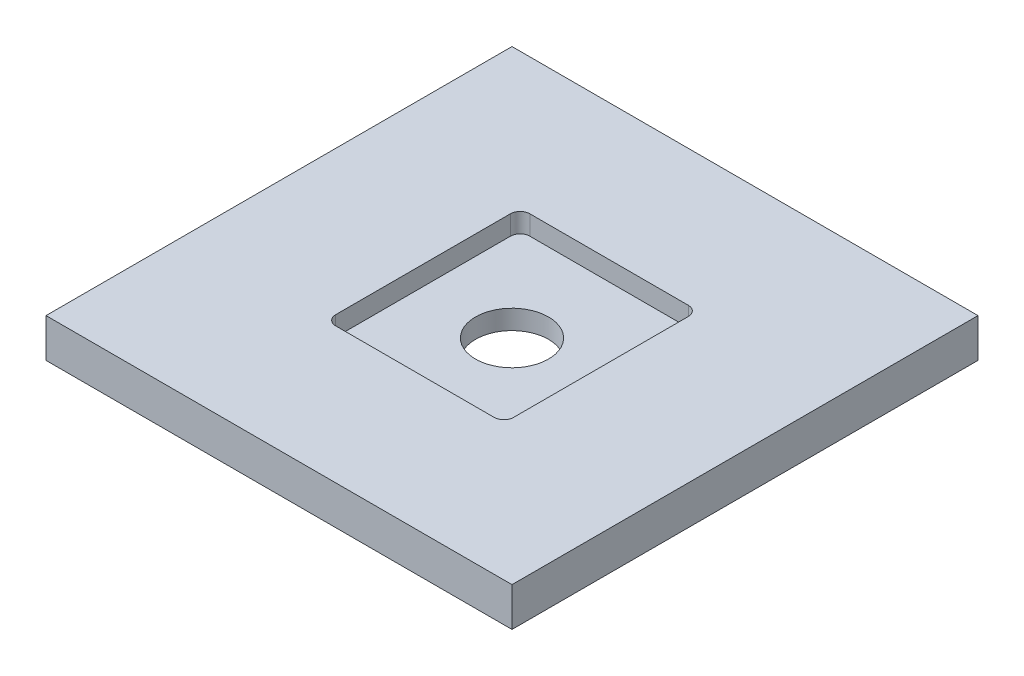
SolidWorks part; units mm, degrees
material "Plain Carbon Steel"
ref_plane "Front Plane" through (0, 0, 0) normal (0, 0, 1) x (1, 0, 0)
ref_plane "Top Plane" through (0, 0, 0) normal (0, 1, 0) x (1, 0, 0)
ref_plane "Right Plane" through (0, 0, 0) normal (1, 0, 0) x (0, 0, -1)
sketch "Sketch1" plane through (0, 0, 0) normal (0, 1, 0) x (1, 0, 0)
  line L1 (-152.4, 152.4) -> (152.4, 152.4)
  line L2 (-152.4, 152.4) -> (-152.4, -152.4)
  line L3 (-152.4, -152.4) -> (152.4, -152.4)
  line L4 (152.4, 152.4) -> (152.4, -152.4)
  line L5 (-152.4, 152.4) -> (152.4, -152.4) construction
  line L6 (-152.4, -152.4) -> (152.4, 152.4) construction
  line L7 (-58.1853, -63.5) -> (58.1853, -63.5)
  line L8 (-58.1853, -63.5) -> (-58.1853, 63.5)
  line L9 (-58.1853, 63.5) -> (58.1853, 63.5)
  line L10 (58.1853, -63.5) -> (58.1853, 63.5)
  line L11 (-58.1853, -63.5) -> (58.1853, 63.5) construction
  line L12 (-58.1853, 63.5) -> (58.1853, -63.5) construction
  point P0 (0, 0)
  point P6 (0, 0)
  dimension "D1" = 304.8
  dimension "D2" = 127
extrude "Sheet metal cutout" add sketch "Sketch1" along normal blind 12.7
fillet "cutout fillet" radius 6.35 4 edges at (-58.1853, 6.35, 63.5) (58.1853, 6.35, 63.5) (58.1853, 6.35, -63.5) (-58.1853, 6.35, -63.5)
sketch "Sketch2" plane through (0, 0, 0) normal (0, -1, 0) x (1, 0, 0)
  line L0 (152.4, -152.4) -> (-152.4, -152.4) construction
  line L1 (152.4, 152.4) -> (-152.4, 152.4)
  line L2 (152.4, 152.4) -> (152.4, -152.4)
  line L3 (152.4, -152.4) -> (-152.4, -152.4)
  line L4 (-152.4, 152.4) -> (-152.4, -152.4)
  line L5 (152.4, 152.4) -> (-152.4, -152.4) construction
  line L6 (152.4, -152.4) -> (-152.4, 152.4) construction
  circle A0 centre (0, 0) radius 23.876
  point P0 (0, 0)
  dimension "D1" = 47.752
extrude "Boss-Extrude2" add sketch "Sketch2" along normal blind 12.7
